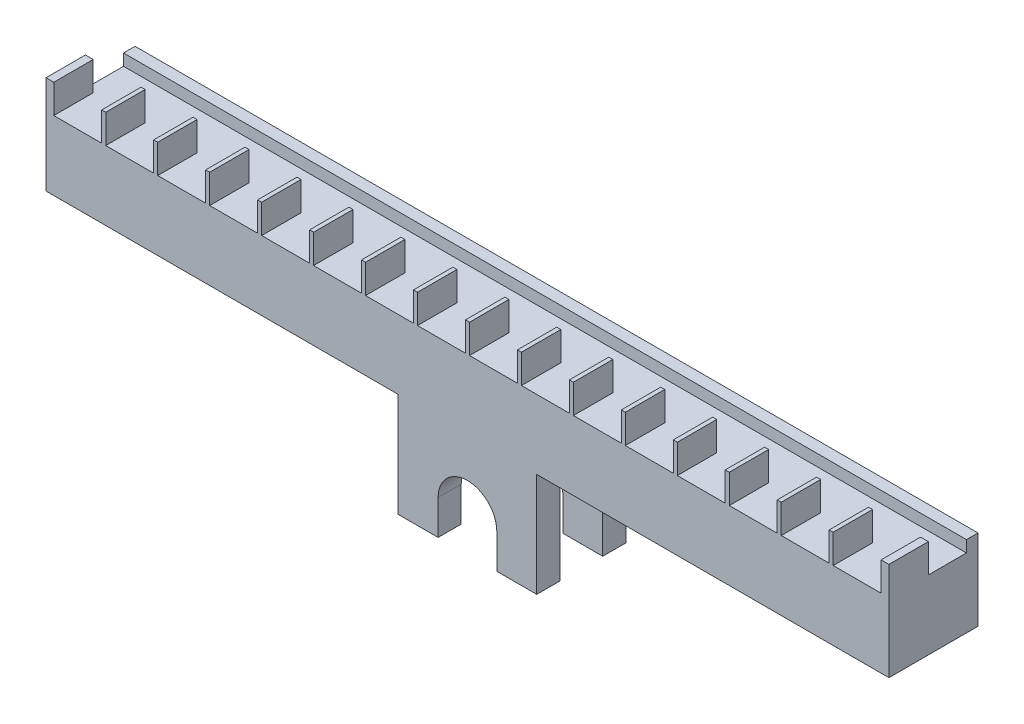
SolidWorks part; units mm, degrees
material "6061-T6 (SS)"
ref_plane "Front" through (0, 0, 0) normal (0, 0, 1) x (1, 0, 0)
ref_plane "Top" through (0, 0, 0) normal (0, 1, 0) x (1, 0, 0)
ref_plane "Right" through (0, 0, 0) normal (1, 0, 0) x (0, 0, -1)
sketch "Sketch1" plane through (0, 0, 0) normal (0, 1, 0) x (1, 0, 0)
  line L1 (-36.5, -7.215) -> (36.5, -7.215)
  line L2 (-36.5, -7.215) -> (-36.5, 0.5)
  line L3 (-36.5, 0.5) -> (36.5, 0.5)
  line L4 (36.5, -7.215) -> (36.5, 0.5)
  point P9 (0, 0.5)
  dimension "D1" = 7.715
  dimension "D2" = 73
  dimension "D3" = 0.5
extrude "Boss-Extrude1" add sketch "Sketch1" along normal blind 6
sketch "Sketch2" plane through (0, 6, 0) normal (0, 1, 0) x (1, 0, 0)
  line L0 (0, 5) -> (0, -49995) construction
  line L1 (36.5, 0.5) -> (-36.5, 0.5) construction
  line L2 (0, -3.3575) -> (50000, -3.3575) construction
  line L3 (-36.5, 0.5) -> (-36.5, -7.215) construction
  line L4 (36.5, -7.215) -> (36.5, 0.5) construction
  line L5 (-36.5, 0.5) -> (36.5, 0.5)
  line L6 (-36.5, 0.5) -> (-36.5, -0.5)
  line L7 (-36.5, -0.5) -> (36.5, -0.5)
  line L8 (36.5, 0.5) -> (36.5, -0.5)
  point P4 (0, 0.5)
  point P11 (-36.5, -3.3575)
  point P17 (-36.5, 0)
  dimension "D1" = 1
extrude "Boss-Extrude2" add sketch "Sketch2" along normal blind 1
sketch "Sketch3" plane through (0, 6, 0) normal (0, 1, 0) x (1, 0, 0)
  line L0 (0, 5) -> (0, -49995) construction
  line L1 (36.5, 0.5) -> (-36.5, 0.5) construction
  line L2 (4.325, 0.5) -> (4.675, 0.5)
  line L3 (-0.175, 0.5) -> (0.175, 0.5)
  line L4 (-0.175, 0.5) -> (-0.175, -7.215)
  line L5 (-0.175, -7.215) -> (0.175, -7.215)
  line L6 (0.175, 0.5) -> (0.175, -7.215)
  line L7 (-36.5, -7.215) -> (36.5, -7.215) construction
  line L8 (4.325, 0.5) -> (4.325, -7.215)
  line L9 (4.325, -7.215) -> (4.675, -7.215)
  line L10 (4.675, 0.5) -> (4.675, -7.215)
  line L11 (8.825, 0.5) -> (9.175, 0.5)
  line L12 (8.825, 0.5) -> (8.825, -7.215)
  line L13 (8.825, -7.215) -> (9.175, -7.215)
  line L14 (9.175, 0.5) -> (9.175, -7.215)
  line L15 (13.325, 0.5) -> (13.675, 0.5)
  line L16 (13.325, 0.5) -> (13.325, -7.215)
  line L17 (13.325, -7.215) -> (13.675, -7.215)
  line L18 (13.675, 0.5) -> (13.675, -7.215)
  line L19 (17.825, 0.5) -> (18.175, 0.5)
  line L20 (17.825, 0.5) -> (17.825, -7.215)
  line L21 (17.825, -7.215) -> (18.175, -7.215)
  line L22 (18.175, 0.5) -> (18.175, -7.215)
  line L23 (22.325, 0.5) -> (22.675, 0.5)
  line L24 (22.325, 0.5) -> (22.325, -7.215)
  line L25 (22.325, -7.215) -> (22.675, -7.215)
  line L26 (22.675, 0.5) -> (22.675, -7.215)
  line L27 (26.825, 0.5) -> (27.175, 0.5)
  line L28 (26.825, 0.5) -> (26.825, -7.215)
  line L29 (26.825, -7.215) -> (27.175, -7.215)
  line L30 (27.175, 0.5) -> (27.175, -7.215)
  line L31 (31.325, 0.5) -> (31.675, 0.5)
  line L32 (31.325, 0.5) -> (31.325, -7.215)
  line L33 (31.325, -7.215) -> (31.675, -7.215)
  line L34 (31.675, 0.5) -> (31.675, -7.215)
  line L35 (35.825, 0.5) -> (36.175, 0.5)
  line L36 (35.825, 0.5) -> (35.825, -7.215)
  line L37 (35.825, -7.215) -> (36.175, -7.215)
  line L38 (36.175, 0.5) -> (36.175, -7.215)
  line L39 (-0.175, 0.5) -> (4.325, 0.5) construction
  line L40 (-4.675, 0.5) -> (-4.325, 0.5)
  line L41 (-4.675, 0.5) -> (-4.675, -7.215)
  line L42 (-4.675, -7.215) -> (-4.325, -7.215)
  line L43 (-4.325, 0.5) -> (-4.325, -7.215)
  line L44 (-9.175, 0.5) -> (-8.825, 0.5)
  line L45 (-9.175, 0.5) -> (-9.175, -7.215)
  line L46 (-9.175, -7.215) -> (-8.825, -7.215)
  line L47 (-8.825, 0.5) -> (-8.825, -7.215)
  line L48 (-13.675, 0.5) -> (-13.325, 0.5)
  line L49 (-13.675, 0.5) -> (-13.675, -7.215)
  line L50 (-13.675, -7.215) -> (-13.325, -7.215)
  line L51 (-13.325, 0.5) -> (-13.325, -7.215)
  line L52 (-18.175, 0.5) -> (-17.825, 0.5)
  line L53 (-18.175, 0.5) -> (-18.175, -7.215)
  line L54 (-18.175, -7.215) -> (-17.825, -7.215)
  line L55 (-17.825, 0.5) -> (-17.825, -7.215)
  line L56 (-22.675, 0.5) -> (-22.325, 0.5)
  line L57 (-22.675, 0.5) -> (-22.675, -7.215)
  line L58 (-22.675, -7.215) -> (-22.325, -7.215)
  line L59 (-22.325, 0.5) -> (-22.325, -7.215)
  line L60 (-27.175, 0.5) -> (-26.825, 0.5)
  line L61 (-27.175, 0.5) -> (-27.175, -7.215)
  line L62 (-27.175, -7.215) -> (-26.825, -7.215)
  line L63 (-26.825, 0.5) -> (-26.825, -7.215)
  line L64 (-31.675, 0.5) -> (-31.325, 0.5)
  line L65 (-31.675, 0.5) -> (-31.675, -7.215)
  line L66 (-31.675, -7.215) -> (-31.325, -7.215)
  line L67 (-31.325, 0.5) -> (-31.325, -7.215)
  line L68 (-36.175, 0.5) -> (-35.825, 0.5)
  line L69 (-36.175, 0.5) -> (-36.175, -7.215)
  line L70 (-36.175, -7.215) -> (-35.825, -7.215)
  line L71 (-35.825, 0.5) -> (-35.825, -7.215)
  line L72 (-0.175, 0.5) -> (-4.675, 0.5) construction
  point P4 (0, 0.5)
  dimension "D1" = 7.715
  dimension "D2" = 0.35
  dimension "D3" = 9
  dimension "D4" = 4.5
  dimension "D6" = 4.5
  dimension "D5" = 9
extrude "Boss-Extrude3" add sketch "Sketch3" along normal offset from surface (2.5 mm away) 8.5 up to face at (0, 0, 3.3575)
sketch "Sketch4" plane through (0, 0, 0) normal (0, 0, 1) x (1, 0, 0)
  line L1 (36.175, 8.5) -> (36.5, 8.5)
  line L2 (36.175, 8.5) -> (36.175, 6)
  line L3 (36.175, 6) -> (36.5, 6)
  line L4 (36.5, 8.5) -> (36.5, 6)
  line L5 (-36.175, 8.5) -> (-36.5, 8.5)
  line L6 (-36.175, 8.5) -> (-36.175, 6)
  line L7 (-36.175, 6) -> (-36.5, 6)
  line L8 (-36.5, 8.5) -> (-36.5, 6)
extrude "Boss-Extrude4" add sketch "Sketch4" along normal up to surface and the other way up to surface up to face at (0, 7.0139, 7.215) other way up to face at (0, 7.5139, -0.5)
sketch "Sketch5" plane through (0, 0, 0) normal (0, 0, 1) x (1, 0, 0)
  line L0 (0, -4.8856) -> (0, -10.2239) construction
  line L1 (-2.54, -6) -> (-2.54, -9)
  line L2 (-6, 0) -> (6, 0)
  line L3 (-6, 0) -> (-6, -9)
  line L4 (-6, -9) -> (-2.54, -9)
  line L5 (6, 0) -> (6, -9)
  line L6 (2.54, -6) -> (2.54, -9)
  line L7 (2.54, -9) -> (6, -9)
  line L8 (-36.5, 0) -> (36.5, 0) construction
  arc A0 (2.54, -6) -> (-2.54, -6) centre (0, -6) ccw
  point P6 (0, 0)
  dimension "D3" = 5.08
  dimension "D1" = 12
  dimension "D2" = 9
  dimension "D4" = 6
extrude "Boss-Extrude5" add sketch "Sketch5" along normal up to surface and the other way up to surface up to face at (0, 7.0735, 7.215) other way up to face at (0, 7.5441, -0.5)
sketch "Sketch6" plane through (0, -9, 0) normal (0, -1, 0) x (1, 0, 0)
  line L0 (-6, 7.215) -> (-6, -0.5) construction
  line L1 (-6, 5.215) -> (6, 5.215)
  line L2 (-6, 5.215) -> (-6, 1.5)
  line L3 (-6, 1.5) -> (6, 1.5)
  line L4 (6, 5.215) -> (6, 1.5)
  line L5 (6, 7.215) -> (6, -0.5) construction
  line L6 (-2.54, 7.215) -> (-6, 7.215) construction
  line L7 (-2.54, -0.5) -> (-6, -0.5) construction
  dimension "D1" = 2
  dimension "D2" = 2
extrude "Cut-Extrude1" cut sketch "Sketch6" against normal up to surface (9 mm away) up to face at (-21.25, 0, 3.3575)
sketch "Sketch7" plane through (0, 0, 0) normal (1, 0, 0) x (0, 0, -1)
  line L0 (0.5, 7) -> (-0.5, 7) construction
  line L1 (0.5, 7) -> (-0.5, 7)
  line L2 (-0.5, 6) -> (-0.5, 7) construction
  line L3 (-0.5, 6) -> (-0.5, 7)
  line L4 (-0.5, 6) -> (-3.802, 6)
  line L5 (-3.802, 6) -> (-3.802, 8.5)
  line L6 (-7.215, 8.5) -> (0.5, 8.5) construction
  line L7 (-3.802, 8.5) -> (0.5, 8.5)
  line L8 (0.5, 8.5) -> (0.5, 7)
  dimension "D1" = 3.302
extrude "Cut-Extrude2" cut sketch "Sketch7" against normal through all both and the other way through all
